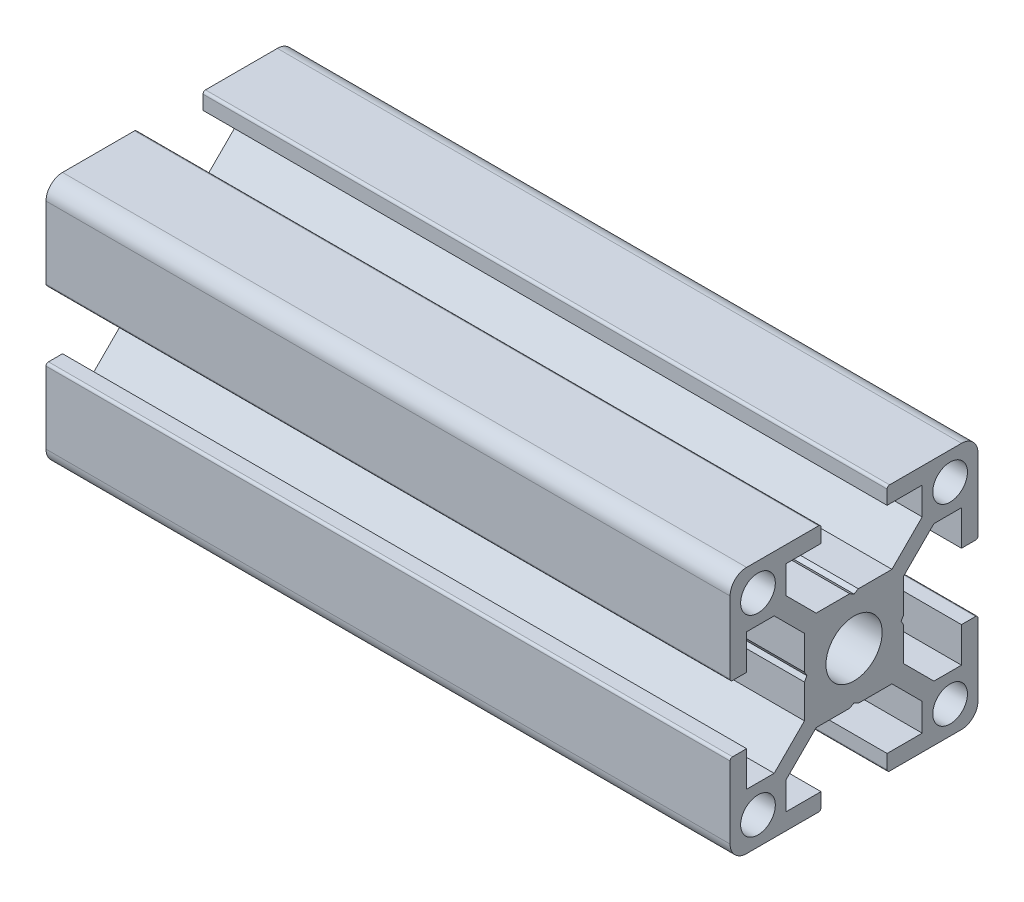
SolidWorks part; units mm, degrees
ref_plane "Front Plane" through (0, 0, 0) normal (0, 0, 1) x (1, 0, 0)
ref_plane "Top Plane" through (0, 0, 0) normal (0, 1, 0) x (1, 0, 0)
ref_plane "Right Plane" through (0, 0, 0) normal (1, 0, 0) x (0, 0, -1)
sketch "Sketch1" plane through (0, 0, 0) normal (0, 0, 1) x (1, 0, 0)
  line L0 (0, 0) -> (82.78, 0)
  dimension "D1" = 82.78
other "30xs6 30X30S6(1)"
ref_plane "Plane1" through (0, 0, 0) normal (1, 0, 0) x (0, 1, 0)
sketch "草图1" plane through (0, 0, 0) normal (1, 0, 0) x (0, 1, 0)
  line L0 (-14.7, 4) -> (-13, 4)
  line L1 (-13, 4) -> (-13, 8.25)
  line L2 (-13, 8.25) -> (-9.6642, 8.25)
  line L3 (-9.6642, 8.25) -> (-6, 4.5858)
  line L4 (-6, 4.5858) -> (-6, 0.5196)
  line L5 (-6, 0.5196) -> (-5.7, 0)
  line L6 (-5.7, 0) -> (-6, -0.5196)
  line L7 (-6, -0.5196) -> (-6, -4.5858)
  line L8 (-6, -4.5858) -> (-9.6642, -8.25)
  line L9 (-9.6642, -8.25) -> (-13, -8.25)
  line L10 (-13, -8.25) -> (-13, -4)
  line L11 (-13, -4) -> (-14.7, -4)
  line L12 (-15, -4.3) -> (-15, -13)
  line L13 (-13, -15) -> (-4.3, -15)
  line L14 (-4, -14.7) -> (-4, -13)
  line L15 (-4, -13) -> (-8.25, -13)
  line L16 (-8.25, -13) -> (-8.25, -9.6642)
  line L17 (-8.25, -9.6642) -> (-4.5858, -6)
  line L18 (-4.5858, -6) -> (-0.5196, -6)
  line L19 (-0.5196, -6) -> (0, -5.7)
  line L20 (0, -5.7) -> (0.5196, -6)
  line L21 (0.5196, -6) -> (4.5858, -6)
  line L22 (4.5858, -6) -> (8.25, -9.6642)
  line L23 (8.25, -9.6642) -> (8.25, -13)
  line L24 (8.25, -13) -> (4, -13)
  line L25 (4, -13) -> (4, -14.7)
  line L26 (4.3, -15) -> (13, -15)
  line L27 (15, -13) -> (15, -4.3)
  line L28 (14.7, -4) -> (13, -4)
  line L29 (13, -4) -> (13, -8.25)
  line L30 (13, -8.25) -> (9.6642, -8.25)
  line L31 (9.6642, -8.25) -> (6, -4.5858)
  line L32 (6, -4.5858) -> (6, -0.5196)
  line L33 (6, -0.5196) -> (5.7, 0)
  line L34 (5.7, 0) -> (6, 0.5196)
  line L35 (6, 0.5196) -> (6, 4.5858)
  line L36 (6, 4.5858) -> (9.6642, 8.25)
  line L37 (9.6642, 8.25) -> (13, 8.25)
  line L38 (13, 8.25) -> (13, 4)
  line L39 (13, 4) -> (14.7, 4)
  line L40 (15, 4.3) -> (15, 13)
  line L41 (13, 15) -> (4.3, 15)
  line L42 (4, 14.7) -> (4, 13)
  line L43 (4, 13) -> (8.25, 13)
  line L44 (8.25, 13) -> (8.25, 9.6642)
  line L45 (8.25, 9.6642) -> (4.5858, 6)
  line L46 (4.5858, 6) -> (0.5196, 6)
  line L47 (0.5196, 6) -> (0, 5.7)
  line L48 (0, 5.7) -> (-0.5196, 6)
  line L49 (-0.5196, 6) -> (-4.5858, 6)
  line L50 (-4.5858, 6) -> (-8.25, 9.6642)
  line L51 (-8.25, 9.6642) -> (-8.25, 13)
  line L52 (-8.25, 13) -> (-4, 13)
  line L53 (-4, 13) -> (-4, 14.7)
  line L54 (-4.3, 15) -> (-13, 15)
  line L55 (-15, 13) -> (-15, 4.3)
  arc A0 (-15, 4.3) -> (-14.7, 4) centre (-14.7, 4.3) ccw
  arc A1 (-14.7, -4) -> (-15, -4.3) centre (-14.7, -4.3) ccw
  arc A2 (-15, -13) -> (-13, -15) centre (-13, -13) ccw
  arc A3 (-4.3, -15) -> (-4, -14.7) centre (-4.3, -14.7) ccw
  arc A4 (4, -14.7) -> (4.3, -15) centre (4.3, -14.7) ccw
  arc A5 (13, -15) -> (15, -13) centre (13, -13) ccw
  arc A6 (15, -4.3) -> (14.7, -4) centre (14.7, -4.3) ccw
  arc A7 (14.7, 4) -> (15, 4.3) centre (14.7, 4.3) ccw
  arc A8 (15, 13) -> (13, 15) centre (13, 13) ccw
  arc A9 (4.3, 15) -> (4, 14.7) centre (4.3, 14.7) ccw
  arc A10 (-4, 14.7) -> (-4.3, 15) centre (-4.3, 14.7) ccw
  arc A11 (-13, 15) -> (-15, 13) centre (-13, 13) ccw
  circle A12 centre (11.625, 11.625) radius 2.1
  circle A13 centre (11.625, -11.625) radius 2.1
  circle A14 centre (0, 0) radius 3.4
  circle A15 centre (-11.625, -11.625) radius 2.1
  circle A16 centre (-11.625, 11.625) radius 2.1
  point P90 (-15, 15)
  point P91 (-0.2598, 14.9121)
  point P92 (15, 15)
  point P93 (15, 0)
  point P94 (15, -15)
  point P95 (0.2598, -15)
  point P96 (-15, -15)
  point P97 (-15, 0)
  point P98 (0, 0)
